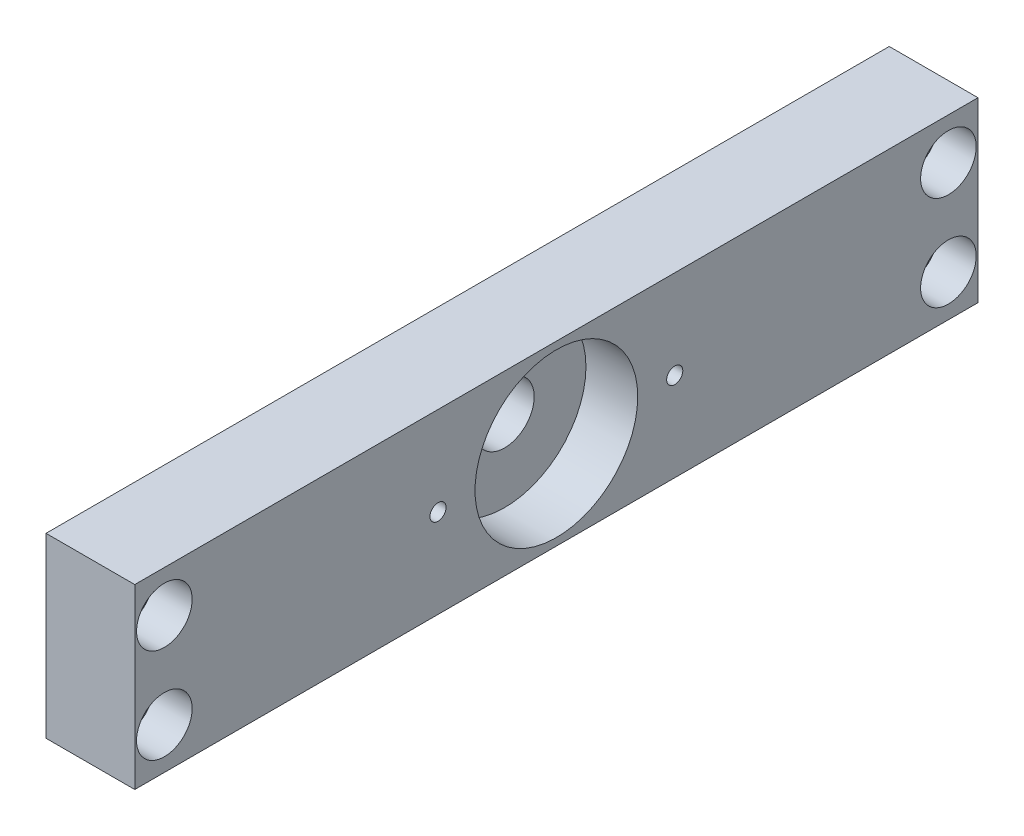
SolidWorks part; units mm, degrees
material "Cast Carbon Steel"
ref_plane "Front Plane" through (0, 0, 0) normal (0, 0, 1) x (1, 0, 0)
ref_plane "Top Plane" through (0, 0, 0) normal (0, 1, 0) x (1, 0, 0)
ref_plane "Right Plane" through (0, 0, 0) normal (1, 0, 0) x (0, 0, -1)
sketch "Sketch1" plane through (0, 0, 0) normal (1, 0, 0) x (0, 0, -1)
  line L0 (0, 19.05) -> (0, -19.05) construction
  line L1 (-90.4875, -19.05) -> (90.4875, -19.05)
  line L2 (-90.4875, -19.05) -> (-90.4875, 19.05)
  line L3 (-90.4875, 19.05) -> (90.4875, 19.05)
  line L4 (90.4875, -19.05) -> (90.4875, 19.05)
  line L5 (-90.4875, -19.05) -> (90.4875, 19.05) construction
  line L6 (-90.4875, 19.05) -> (90.4875, -19.05) construction
  line L7 (-90.4875, 0) -> (90.4875, 0) construction
  circle A0 centre (0, 0) radius 6.35
  circle A1 centre (-25.4, 0) radius 1.7272
  circle A2 centre (-84.1375, 10.16) radius 4.2164
  circle A3 centre (-84.1375, -10.16) radius 4.2164
  circle A4 centre (25.4, 0) radius 1.7272
  circle A5 centre (84.1375, -10.16) radius 4.2164
  circle A6 centre (84.1375, 10.16) radius 4.2164
  point P0 (0, 0)
  dimension "D3" = 12.7
  dimension "D4" = 3.4544
  dimension "D5" = 25.4
  dimension "D6" = 84.1375
  dimension "D7" = 8.4328
  dimension "D8" = 10.16
  dimension "D1" = 38.1
  dimension "D2" = 180.975
extrude "Boss-Extrude1" add sketch "Sketch1" along normal blind 19.05
sketch "Sketch2" plane through (19.05, 0, 0) normal (1, 0, 0) x (0, 0, -1)
  line L0 (-90.4875, 0) -> (90.4875, 0) construction
  line L1 (-90.4875, 19.05) -> (-90.4875, -19.05) construction
  line L2 (90.4875, -19.05) -> (90.4875, 19.05) construction
  line L3 (0, 19.05) -> (0, -19.05) construction
  line L4 (90.4875, 19.05) -> (-90.4875, 19.05) construction
  line L5 (-90.4875, -19.05) -> (90.4875, -19.05) construction
  circle A0 centre (-84.1375, 10.16) radius 5.969
  circle A1 centre (-84.1375, -10.16) radius 5.969
  circle A2 centre (84.1375, -10.16) radius 5.969
  circle A3 centre (84.1375, 10.16) radius 5.969
  dimension "D1" = 11.938
extrude "Cut-Extrude2" cut sketch "Sketch2" against normal blind 8.255
sketch "Sketch3" plane through (19.05, 0, 0) normal (1, 0, 0) x (0, 0, -1)
  circle A0 centre (0, 0) radius 17.4625
  dimension "D1" = 34.925
extrude "Cut-Extrude3" cut sketch "Sketch3" against normal blind 11.1125
